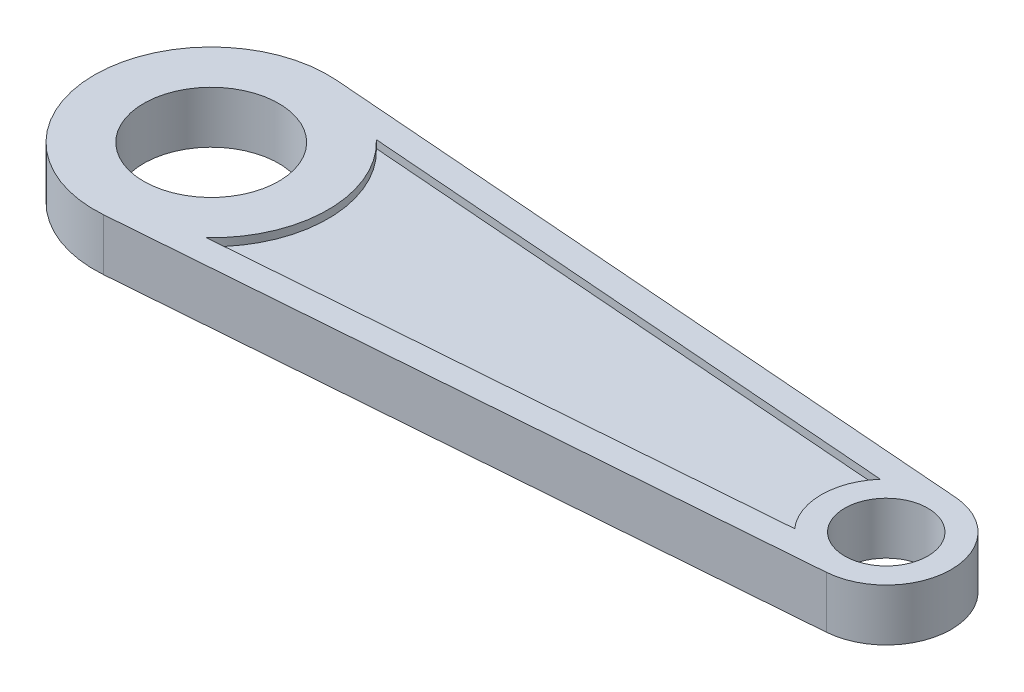
SolidWorks part; units mm, degrees
material "Plain Carbon Steel"
ref_plane "Front Plane" through (0, 0, 0) normal (0, 0, 1) x (1, 0, 0)
ref_plane "Top Plane" through (0, 0, 0) normal (0, 1, 0) x (1, 0, 0)
ref_plane "Right Plane" through (0, 0, 0) normal (1, 0, 0) x (0, 0, -1)
sketch "Sketch1" plane through (0, 0, 0) normal (0, 1, 0) x (1, 0, 0)
  line L0 (0, 0) -> (130, 0) construction
  line L1 (1.7308, 22.4333) -> (130.9615, 12.463)
  line L2 (1.7308, -22.4333) -> (130.9615, -12.463)
  circle A0 centre (0, 0) radius 22.5
  circle A1 centre (130, 0) radius 12.5
  circle A2 centre (0, 0) radius 13
  circle A3 centre (130, 0) radius 8
  dimension "D1" = 45
  dimension "D2" = 25
  dimension "D4" = 16
  dimension "D5" = 26
  dimension "D3" = 130
extrude "Boss-Extrude2" add sketch "Sketch1" along normal blind 10
sketch "Sketch3" plane through (0, 10, 0) normal (0, 1, 0) x (1, 0, 0)
  line L0 (15.4464, 16.3603) -> (120.6066, 8.247)
  line L1 (1.7308, 22.4333) -> (130.9615, 12.463) construction
  line L2 (15.4464, -16.3603) -> (120.6066, -8.247)
  line L3 (1.7308, -22.4333) -> (130.9615, -12.463) construction
  arc A0 (15.4464, -16.3603) -> (15.4464, 16.3603) centre (0, 0) ccw
  arc A1 (120.6066, 8.247) -> (120.6066, -8.247) centre (130, 0) ccw
  point P8 (1.3462, 17.4481)
  point P9 (130.5769, 7.4778)
  dimension "D1" = 45
  dimension "D2" = 25
  dimension "D3" = 5
  dimension "D4" = 5
extrude "Cut-Extrude1" cut sketch "Sketch3" against normal blind 1.5
sketch "Sketch5" plane through (0, 0, 0) normal (0, -1, 0) x (1, 0, 0)
  line L4 (15.4464, 16.3603) -> (120.6066, 8.247)
  line L6 (15.4464, -16.3603) -> (120.6066, -8.247)
  line L7 (1.7308, 22.4333) -> (130.9615, 12.463) construction
  line L8 (1.7308, -22.4333) -> (130.9615, -12.463) construction
  arc A2 (15.4464, -16.3603) -> (15.4464, 16.3603) centre (0, 0) ccw
  arc A3 (120.6066, 8.247) -> (120.6066, -8.247) centre (130, 0) ccw
  point P10 (1.3462, 17.4481)
  point P11 (130.5769, 7.4778)
  dimension "D1" = 22.5
  dimension "D2" = 12.5
  dimension "D3" = 5
  dimension "D4" = 5
extrude "Cut-Extrude2" cut sketch "Sketch5" against normal blind 1.5
